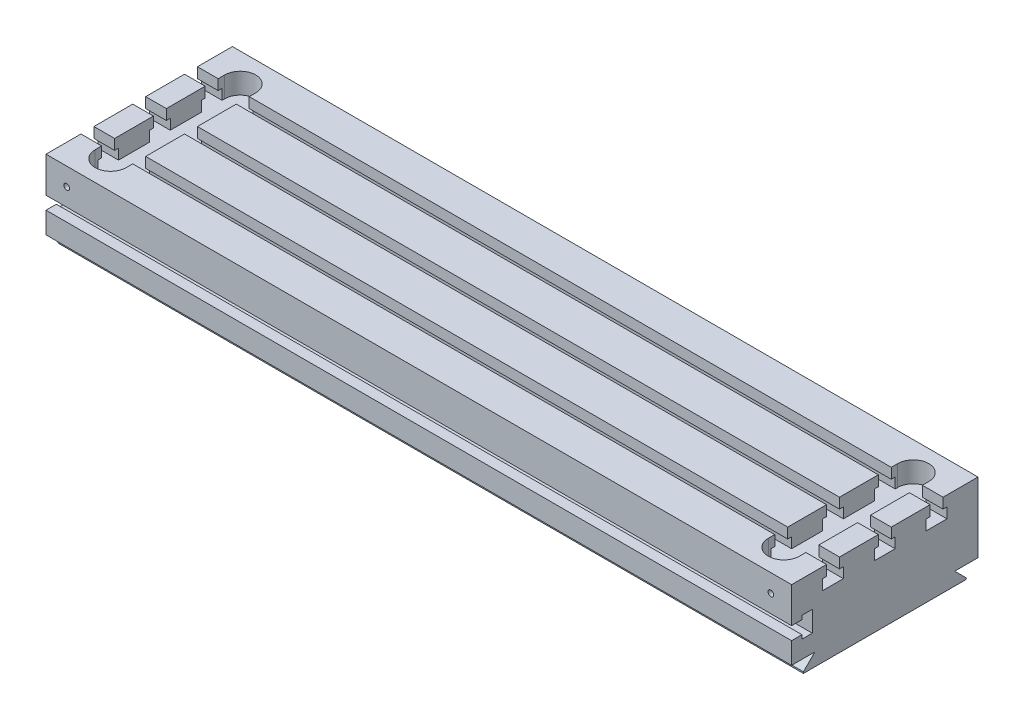
SolidWorks part; units mm, degrees
ref_plane "Front Plane" through (0, 0, 0) normal (0, 0, 1) x (1, 0, 0)
ref_plane "Top Plane" through (0, 0, 0) normal (0, 1, 0) x (1, 0, 0)
ref_plane "Right Plane" through (0, 0, 0) normal (1, 0, 0) x (0, 0, -1)
other "Configuration Table"
sketch "Sketch1" plane through (0, 0, 0) normal (0, 1, 0) x (1, 0, 0)
  line L0 (-457.2, -114.3) -> (457.2, 114.3) construction
  line L1 (-457.2, 114.3) -> (457.2, 114.3)
  line L2 (-457.2, 114.3) -> (-457.2, -114.3)
  line L3 (-457.2, -114.3) -> (457.2, -114.3)
  line L4 (457.2, 114.3) -> (457.2, -114.3)
  dimension "D1" = 914.4
  dimension "D2" = 228.6
extrude "Extrude1" add sketch "Sketch1" against normal blind 85.725
sketch "Sketch2" plane through (0, 0, 0) normal (1, 0, 0) x (0, 0, -1)
  line L0 (-114.3, 0) -> (114.3, 0) construction
  line L9 (12.7, -25.4) -> (12.7, -12.7)
  line L10 (12.7, -12.7) -> (7.9375, -12.7)
  line L11 (-12.7, -25.4) -> (12.7, -25.4)
  line L12 (7.9375, -12.7) -> (7.9375, 0)
  line L13 (-7.9375, 0) -> (-7.9375, -12.7)
  line L14 (-12.7, -12.7) -> (-12.7, -25.4)
  line L15 (7.9375, 0) -> (-7.9375, 0)
  line L16 (-7.9375, -12.7) -> (-12.7, -12.7)
  dimension "D1" = 12.7
  dimension "D2" = 12.7
  dimension "D3" = 25.4
  dimension "D4" = 15.875
extrude "Cut-Extrude1" cut sketch "Sketch2" against normal through all and the other way through all
pattern_linear "LPattern1" count 2 spacing 63.5 along (0, 0, -1) count 2 spacing 63.5 along (0, 0, 1) of "Cut-Extrude1"
sketch "Sketch3" plane through (0, 0, 0) normal (1, 0, 0) x (0, 0, -1)
  line L1 (-114.3, -59.5166) -> (-101.6, -59.5166)
  line L2 (-88.9, -64.2791) -> (-88.9, -38.8791)
  line L3 (-88.9, -38.8791) -> (-101.6, -38.8791)
  line L4 (-114.3, -43.6416) -> (-114.3, -59.5166)
  line L5 (-101.6, -64.2791) -> (-88.9, -64.2791)
  line L6 (-101.6, -59.5166) -> (-101.6, -64.2791)
  line L7 (-101.6, -38.8791) -> (-101.6, -43.6416)
  line L8 (-101.6, -43.6416) -> (-114.3, -43.6416)
  line L9 (-114.3, -85.725) -> (-114.3, 0) construction
  line L13 (-71.4375, 0) -> (-71.4375, -12.7) construction
  line L14 (-76.2, -12.7) -> (-76.2, -25.4) construction
  line L15 (-76.2, -25.4) -> (-50.8, -25.4) construction
  line L16 (-114.3, 0) -> (-71.4375, 0) construction
  dimension "D1" = 43.6416
  dimension "D2" = 15.875
extrude "Cut-Extrude2" cut sketch "Sketch3" against normal through all and the other way through all
sketch "Sketch4" plane through (0, 0, 0) normal (1, 0, 0) x (0, 0, -1)
  line L0 (-85.725, -85.725) -> (-101.6, -101.6)
  line L1 (-114.3, -85.725) -> (114.3, -85.725) construction
  line L2 (-101.6, -101.6) -> (101.6, -101.6)
  line L3 (101.6, -101.6) -> (85.725, -85.725)
  line L4 (0, 0) -> (0, -101.6) construction
  line L41 (-114.3, -43.6416) -> (-101.6, -43.6416)
  line L42 (-101.6, -43.6416) -> (-101.6, -38.8791)
  line L43 (-101.6, -38.8791) -> (-88.9, -38.8791)
  line L44 (-88.9, -38.8791) -> (-88.9, -64.2791)
  line L45 (-88.9, -64.2791) -> (-101.6, -64.2791)
  line L46 (-101.6, -64.2791) -> (-101.6, -59.5166)
  line L47 (-101.6, -59.5166) -> (-114.3, -59.5166)
  line L48 (-114.3, -59.5166) -> (-114.3, -85.725)
  line L49 (-114.3, -85.725) -> (114.3, -85.725)
  line L50 (114.3, -85.725) -> (114.3, 0)
  line L51 (114.3, 0) -> (71.4375, 0)
  line L52 (71.4375, 0) -> (71.4375, -12.7)
  line L53 (71.4375, -12.7) -> (76.2, -12.7)
  line L54 (76.2, -12.7) -> (76.2, -25.4)
  line L55 (76.2, -25.4) -> (50.8, -25.4)
  line L56 (50.8, -25.4) -> (50.8, -12.7)
  line L57 (50.8, -12.7) -> (55.5625, -12.7)
  line L58 (55.5625, -12.7) -> (55.5625, 0)
  line L59 (55.5625, 0) -> (7.9375, 0)
  line L60 (7.9375, 0) -> (7.9375, -12.7)
  line L61 (7.9375, -12.7) -> (12.7, -12.7)
  line L62 (12.7, -12.7) -> (12.7, -25.4)
  line L63 (12.7, -25.4) -> (-12.7, -25.4)
  line L64 (-12.7, -25.4) -> (-12.7, -12.7)
  line L65 (-12.7, -12.7) -> (-7.9375, -12.7)
  line L66 (-7.9375, -12.7) -> (-7.9375, 0)
  line L67 (-7.9375, 0) -> (-55.5625, 0)
  line L68 (-55.5625, 0) -> (-55.5625, -12.7)
  line L69 (-55.5625, -12.7) -> (-50.8, -12.7)
  line L70 (-50.8, -12.7) -> (-50.8, -25.4)
  line L71 (-50.8, -25.4) -> (-76.2, -25.4)
  line L72 (-76.2, -25.4) -> (-76.2, -12.7)
  line L73 (-76.2, -12.7) -> (-71.4375, -12.7)
  line L74 (-71.4375, -12.7) -> (-71.4375, 0)
  line L75 (-71.4375, 0) -> (-114.3, 0)
  line L76 (-114.3, 0) -> (-114.3, -43.6416)
  line L85 (-85.725, -85.725) -> (85.725, -85.725)
  dimension "D1" = 45
  dimension "D2" = 203.2
  dimension "D3" = 15.875
  dimension "D4" = 0
extrude "Extrude2" add sketch "Sketch4" along normal through all and the other way through all
chamfer "Chamfer1" distance 2.54 angle 45 2 edges at (0, -101.6, -101.6) (0, -101.6, 101.6)
sketch "Sketch5" plane through (0, 0, 0) normal (0, 1, 0) x (-1, 0, 0)
  line L0 (393.7, 0) -> (0, 0) construction
  line L1 (457.2, 7.9375) -> (457.2, 55.5625) construction
  line L2 (431.8, -79.375) -> (431.8, 79.375)
  line L4 (393.7, -79.375) -> (393.7, 79.375)
  arc A0 (431.8, -79.375) -> (393.7, -79.375) centre (412.75, -79.375) cw
  arc A1 (431.8, 79.375) -> (393.7, 79.375) centre (412.75, 79.375) ccw
  dimension "D1" = 158.75
  dimension "D2" = 38.1
  dimension "D3" = 25.4
extrude "Cut-Extrude3" cut sketch "Sketch5" against normal up to surface (25.4 mm away) up to face at (0, -25.4, 63.5)
mirror "Mirror1" about plane through (0, 0, 0) normal (1, 0, 0) of "Cut-Extrude3"
hole_wizard "M8x1.0 Tapped Hole1" positions "3DSketch1" profile "Sketch6" tap size "M8x1.0" standard "Ansi Metric"
sketch3d "3DSketch1"
  line L0 (-457.2, -43.6416, 114.3) -> (-457.2, 0, 114.3) construction
  line L1 (457.2, -43.6416, 114.3) -> (457.2, 0, 114.3) construction
  line L2 (-457.2, 0, 114.3) -> (457.2, 0, 114.3) construction
  point P0 (431.8, -22, 114.3)
  point P4 (-431.8, -22, 114.3)
  dimension "D1" = 25.4
  dimension "D2" = 25.4
  dimension "D3" = 22
sketch "Sketch6" plane through (431.8, -22, 114.3) normal (1, 0, 0) x (0, -1, 0)
  line L0 (0, 0) -> (0, 20.103)
  line L1 (0, 20.103) -> (3.5, 18)
  line L2 (3.5, 18) -> (3.5, 0)
  line L5 (3.5, 0) -> (0, 0)
  line L10 (0, 20.103) -> (-3.5, 18) construction
  line L11 (0, -6.35) -> (0, 107.95) construction
  dimension "Tap Drill Dia." = 7
  dimension "Tap Drill Depth" = 18
  dimension "Drill Angle" = 118
cosmetic thread "Hole Thread1" parameters "D1"=16, "D2"=8
cosmetic thread "Hole Thread2" parameters "D1"=16, "D2"=8
mirror "Mirror2" about plane through (0, 0, 0) normal (0, 0, 1) of "M8x1.0 Tapped Hole1"
